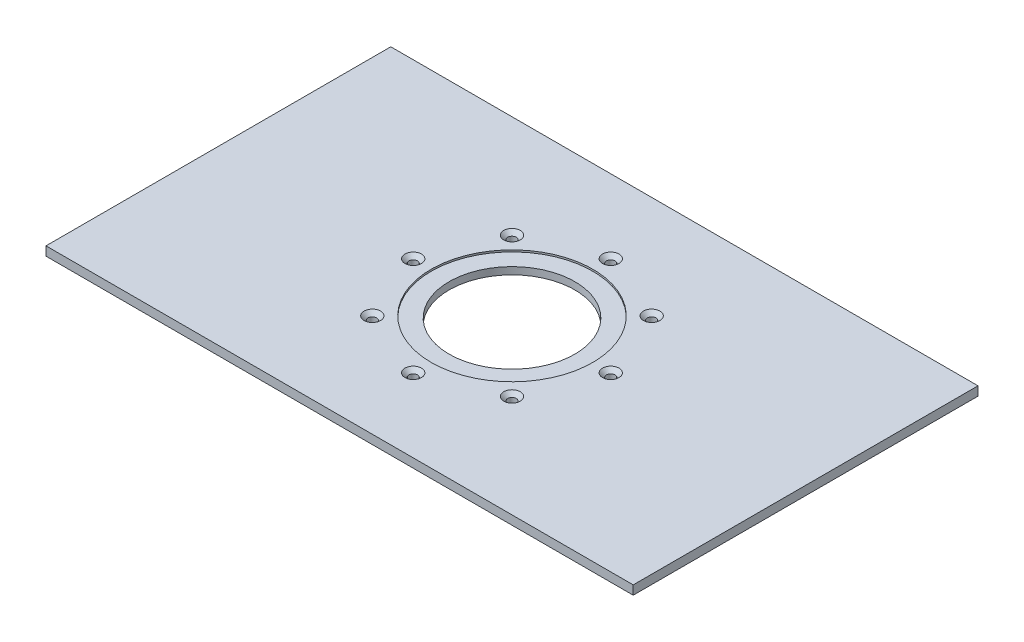
SolidWorks part; units mm, degrees
material "6061-T6 (SS)"
ref_plane "Front Plane" through (0, 0, 0) normal (0, 0, 1) x (1, 0, 0)
ref_plane "Top Plane" through (0, 0, 0) normal (0, 1, 0) x (1, 0, 0)
ref_plane "Right Plane" through (0, 0, 0) normal (1, 0, 0) x (0, 0, -1)
sketch "Sketch1" plane through (0, 0, 0) normal (0, 1, 0) x (1, 0, 0)
  line L1 (-163.5, -96) -> (163.5, -96)
  line L2 (-163.5, -96) -> (-163.5, 96)
  line L3 (-163.5, 96) -> (163.5, 96)
  line L4 (163.5, -96) -> (163.5, 96)
  line L5 (-163.5, -96) -> (163.5, 96) construction
  line L6 (-163.5, 96) -> (163.5, -96) construction
  point P0 (0, 0)
  dimension "D1" = 192
  dimension "D2" = 327
extrude "Boss-Extrude1" add sketch "Sketch1" along normal blind 5
sketch "Sketch2" plane through (0, 5, 0) normal (0, 1, 0) x (1, 0, 0)
  circle A0 centre (0, 0) radius 35
  dimension "D1" = 70
extrude "Cut-Extrude1" cut sketch "Sketch2" against normal through all
sketch "Sketch3" plane through (0, 5, 0) normal (0, 1, 0) x (1, 0, 0)
  circle A0 centre (0, 0) radius 45
  dimension "D1" = 90
extrude "Cut-Extrude2" cut sketch "Sketch3" against normal blind 1
sketch "Sketch6" plane through (0, 5, 0) normal (0, 1, 0) x (1, 0, 0)
  circle A0 centre (0, 0) radius 55
  point P4 (-55, 0)
  point P10 (-38.8909, 38.8909)
  point P11 (0, 55)
  point P12 (38.8909, 38.8909)
  point P13 (55, 0)
  point P14 (38.8909, -38.8909)
  point P15 (0, -55)
  point P16 (-38.8909, -38.8909)
  dimension "D1" = 110
  dimension "D2" = 8
hole_wizard "CSK for M4 Hex Socket Countersunk Head Screw1" positions "Sketch6" profile "Sketch5" countersink size "M4" standard "DIN" end condition through all
sketch "Sketch5" plane through (-38.8909, 5, 38.8909) normal (1, 0, 0) x (0, 0, 1)
  line L0 (0, 0) -> (0, 5)
  line L1 (0, 5) -> (2.4, 5)
  line L2 (2.4, 5) -> (2.4, 2.19)
  line L3 (2.4, 2.19) -> (4.59, 0)
  line L5 (4.59, 0) -> (0, 0)
  line L6 (-2.4, 2.19) -> (-4.59, 0) construction
  line L11 (0, -6.35) -> (0, 107.95) construction
  dimension "Thru Hole Dia." = 4.8
  dimension "Thru Hole Depth" = 5
  dimension "Near C'Sink Dia." = 9.18
  dimension "Near C'Sink Angle" = 90
